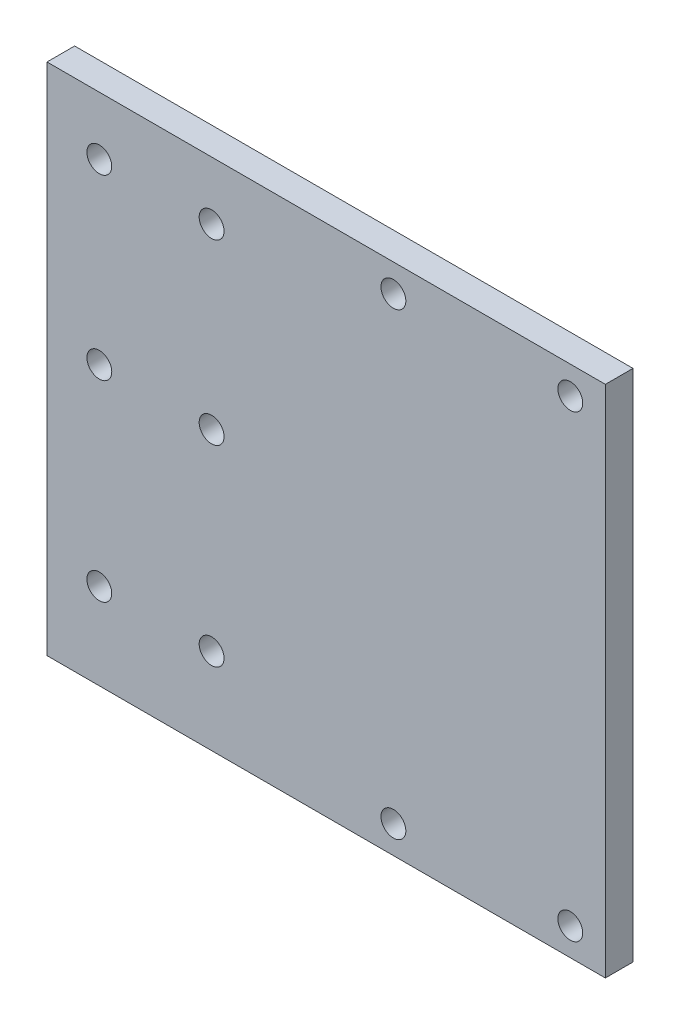
SolidWorks part; units mm, degrees
ref_plane "Plan de face" through (0, 0, 0) normal (0, 0, 1) x (1, 0, 0)
ref_plane "Plan de dessus" through (0, 0, 0) normal (0, 1, 0) x (1, 0, 0)
ref_plane "Plan de droite" through (0, 0, 0) normal (1, 0, 0) x (0, 0, -1)
sketch "Esquisse1" plane through (0, 0, 0) normal (0, 0, 1) x (1, 0, 0)
  line L1 (-50.5, -46.5) -> (50.5, -46.5)
  line L2 (-50.5, -46.5) -> (-50.5, 46.5)
  line L3 (-50.5, 46.5) -> (50.5, 46.5)
  line L4 (50.5, -46.5) -> (50.5, 46.5)
  line L5 (-50.5, -46.5) -> (50.5, 46.5) construction
  line L6 (-50.5, 46.5) -> (50.5, -46.5) construction
  point P0 (0, 0)
  dimension "D1" = 93
  dimension "D2" = 101
extrude "Boss.-Extru.1" add sketch "Esquisse1" along normal blind 5
hole_wizard "Dégagement M41" positions "Esquisse3" profile "Esquisse2" hole size "M4" standard "JIS" end condition through all
sketch "Esquisse3" plane through (0, 0, 5) normal (0, 0, 1) x (1, 0, 0)
  point P0 (44.1579, 41.5)
  point P1 (12.1579, 41.5)
  point P3 (12.1579, -41.5)
  point P5 (44.1579, -41.5)
sketch "Esquisse2" plane through (44.1579, 41.5, 5) normal (1, 0, 0) x (0, -1, 0)
  line L0 (0, 0) -> (0, 5)
  line L1 (0, 5) -> (2.25, 5)
  line L2 (2.25, 5) -> (2.25, 0)
  line L5 (2.25, 0) -> (0, 0)
  line L11 (0, -6.35) -> (0, 107.95) construction
  dimension "Diamètre du perçage jusqu'au prochain" = 4.5
  dimension "Profondeur du perçage jusqu'au prochain" = 5
hole_wizard "Dégagement M42" positions "Esquisse5" profile "Esquisse4" hole size "M4" standard "JIS" end condition through all
sketch "Esquisse5" plane through (0, 0, 5) normal (0, 0, 1) x (1, 0, 0)
  point P0 (-20.7231, -30.9129)
  point P2 (-20.7231, 3.8035)
  point P4 (-41.0358, 3.8035)
  point P6 (-41.0358, -30.9129)
  point P8 (-41.0358, 35.9838)
  point P10 (-20.7231, 35.9838)
sketch "Esquisse4" plane through (-20.7231, -30.9129, 5) normal (1, 0, 0) x (0, -1, 0)
  line L0 (0, 0) -> (0, 5)
  line L1 (0, 5) -> (2.25, 5)
  line L2 (2.25, 5) -> (2.25, 0)
  line L5 (2.25, 0) -> (0, 0)
  line L11 (0, -6.35) -> (0, 107.95) construction
  dimension "Diamètre du perçage jusqu'au prochain" = 4.5
  dimension "Profondeur du perçage jusqu'au prochain" = 5
